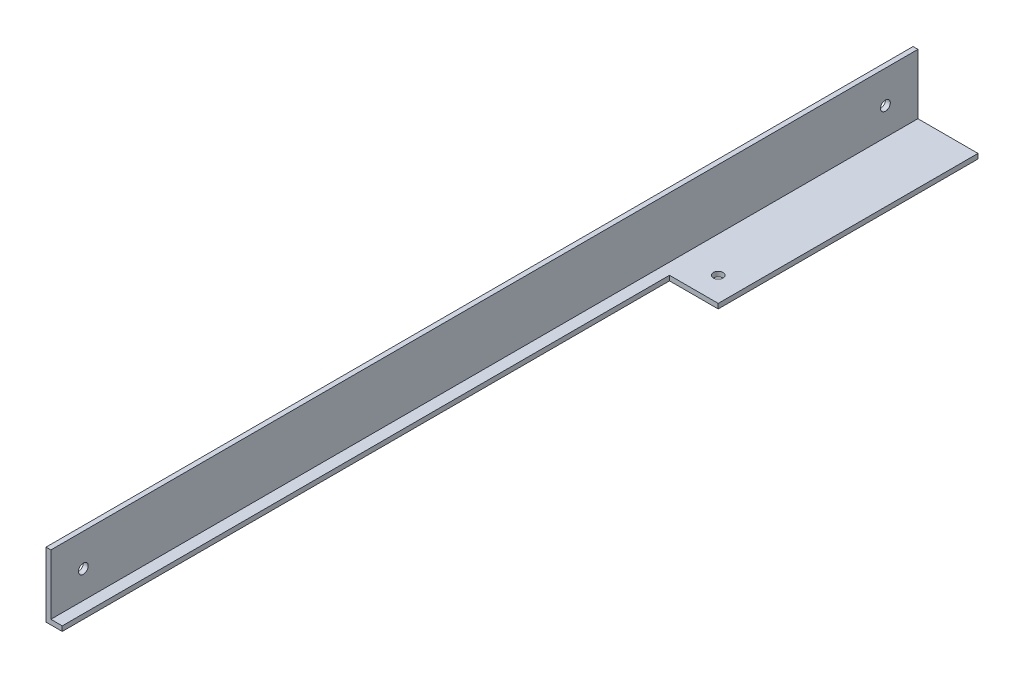
SolidWorks part; units mm, degrees
ref_plane "Plan de face" through (0, 0, 0) normal (0, 0, 1) x (1, 0, 0)
ref_plane "Plan de dessus" through (0, 0, 0) normal (0, 1, 0) x (1, 0, 0)
ref_plane "Plan de droite" through (0, 0, 0) normal (1, 0, 0) x (0, 0, -1)
sketch "Esquisse1" plane through (0, 0, 0) normal (0, 0, 1) x (1, 0, 0)
  line L0 (0, 0) -> (20, 0)
  line L1 (20, 0) -> (20, 1.5)
  line L2 (20, 1.5) -> (1.5, 1.5)
  line L3 (1.5, 1.5) -> (1.5, 20)
  line L4 (1.5, 20) -> (0, 20)
  line L5 (0, 20) -> (0, 0)
  dimension "D1" = 1.5
  dimension "D2" = 1.5
  dimension "D3" = 20
  dimension "D4" = 20
extrude "Extrusion1" add sketch "Esquisse1" along normal blind 267
sketch "Esquisse2" plane through (0, 1.5, 0) normal (0, 1, 0) x (1, 0, 0)
  line L0 (20, -267) -> (20, 0) construction
  line L3 (0, -267) -> (20, -267) construction
  line L4 (20, -267) -> (5, -267)
  line L5 (20, -267) -> (20, -80)
  line L6 (20, -80) -> (5, -80)
  line L7 (5, -267) -> (5, -80)
  line L8 (0, -267) -> (0, 0) construction
  line L9 (20, -267) -> (20, 0) construction
  circle A0 centre (12.5, -72.5) radius 1.5
  dimension "D3" = 0
  dimension "D4" = 5
  dimension "D7" = 0
  dimension "D1" = 7.5
  dimension "D2" = 7.5
  dimension "D8" = 187
extrude "Extrusion2" cut sketch "Esquisse2" against normal through all
sketch "Esquisse3" plane through (1.5, 0, 0) normal (1, 0, 0) x (0, 0, -1)
  line L0 (-257, 10) -> (-10, 10) construction
  line L1 (-267, 20) -> (0, 20) construction
  line L2 (-267, 1.5) -> (-267, 20) construction
  line L3 (0, 1.5) -> (0, 20) construction
  circle A0 centre (-257, 10) radius 1.5
  circle A1 centre (-10, 10) radius 1.5
  dimension "D2" = 10
  dimension "D1" = 10
  dimension "D3" = 10
extrude "Extrusion3" cut sketch "Esquisse3" against normal blind 264
